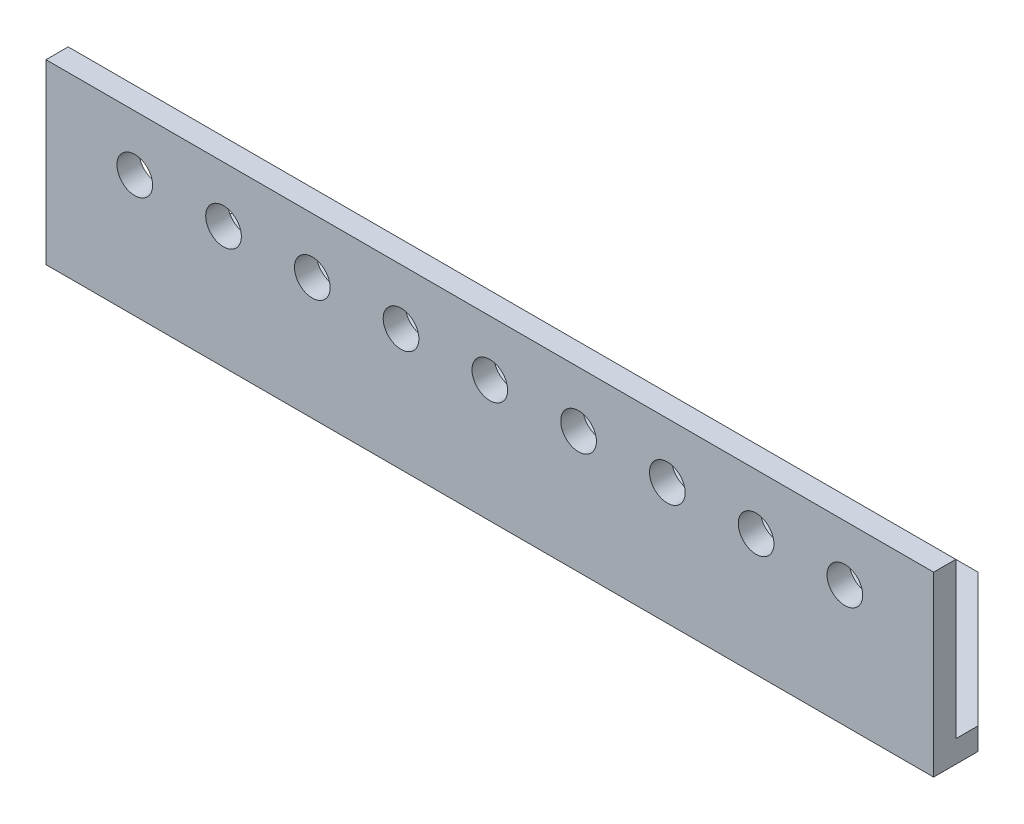
SolidWorks part; units mm, degrees
material "6061-T6 (SS)"
ref_plane "Front Plane" through (0, 0, 0) normal (0, 0, 1) x (1, 0, 0)
ref_plane "Top Plane" through (0, 0, 0) normal (0, 1, 0) x (1, 0, 0)
ref_plane "Right Plane" through (0, 0, 0) normal (1, 0, 0) x (0, 0, -1)
sketch "Sketch2" plane through (0, 0, 0) normal (0, 1, 0) x (1, 0, 0)
  line L0 (0, 0) -> (12.7, 0) construction
  line L1 (0, 0) -> (-12.7, 0) construction
  line L2 (6.35, 0) -> (6.35, 12.7) construction
  line L3 (-57.15, 12.7) -> (69.85, 12.7)
  line L4 (-57.15, 12.7) -> (-57.15, -12.7)
  line L5 (-57.15, -12.7) -> (69.85, -12.7)
  line L6 (69.85, 12.7) -> (69.85, -12.7)
  circle A0 centre (0, 0) radius 2.5527
  circle A1 centre (12.7, 0) radius 2.5527
  circle A2 centre (25.4, 0) radius 2.5527
  circle A3 centre (38.1, 0) radius 2.5527
  circle A4 centre (-12.7, 0) radius 2.5527
  circle A5 centre (-25.4, 0) radius 2.5527
  circle A6 centre (-38.1, 0) radius 2.5527
  circle A7 centre (50.8, 0) radius 2.5527
  dimension "D1" = 5.1054
  dimension "D3" = 12.7
  dimension "D5" = 12.7
  dimension "D6" = 25.4
  dimension "D7" = 12.7
  dimension "D8" = 127
  dimension "D2" = 5
  dimension "D4" = 4
extrude "Boss-Extrude1" add sketch "Sketch2" along normal blind 3.175
sketch "Sketch4" plane through (0, 0, 12.7) normal (0, 0, 1) x (1, 0, 0)
  line L0 (6.35, 17.4625) -> (19.05, 17.4625) construction
  line L1 (-57.15, 3.175) -> (69.85, 3.175)
  line L2 (-57.15, 3.175) -> (-57.15, 25.4)
  line L3 (-57.15, 25.4) -> (69.85, 25.4)
  line L4 (69.85, 3.175) -> (69.85, 25.4)
  line L5 (6.35, 0) -> (6.35, 17.4625) construction
  line L6 (-57.15, 0) -> (69.85, 0) construction
  circle A0 centre (6.35, 17.4625) radius 2.5527
  circle A1 centre (19.05, 17.4625) radius 2.5527
  circle A2 centre (31.75, 17.4625) radius 2.5527
  circle A3 centre (44.45, 17.4625) radius 2.5527
  circle A4 centre (57.15, 17.4625) radius 2.5527
  circle A10 centre (-44.45, 17.4625) radius 2.5527
  circle A11 centre (-31.75, 17.4625) radius 2.5527
  circle A12 centre (-19.05, 17.4625) radius 2.5527
  circle A13 centre (-6.35, 17.4625) radius 2.5527
  dimension "D3" = 5.1054
  dimension "D1" = 22.225
  dimension "D2" = 7.9375
  dimension "D5" = 12.7
  dimension "D4" = 5
extrude "Boss-Extrude3" add sketch "Sketch4" against normal blind 3.175
sketch "Sketch5" plane through (0, 3.175, 0) normal (0, 1, 0) x (1, 0, 0)
  line L0 (-38.1, 12.7) -> (-57.15, -6.35)
  line L1 (69.85, 12.7) -> (-57.15, 12.7) construction
  line L2 (-57.15, 12.7) -> (-57.15, -9.525) construction
  line L3 (50.8, 12.7) -> (69.85, -6.35)
  line L5 (69.85, -6.35) -> (69.85, 12.7)
  line L6 (69.85, 12.7) -> (50.8, 12.7)
  line L7 (-38.1, 12.7) -> (-57.15, 12.7)
  line L8 (-57.15, 12.7) -> (-57.15, -6.35)
  line L9 (69.85, -9.525) -> (69.85, 12.7) construction
  dimension "D1" = 19.05
extrude "Cut-Extrude1" cut sketch "Sketch5" against normal through all
